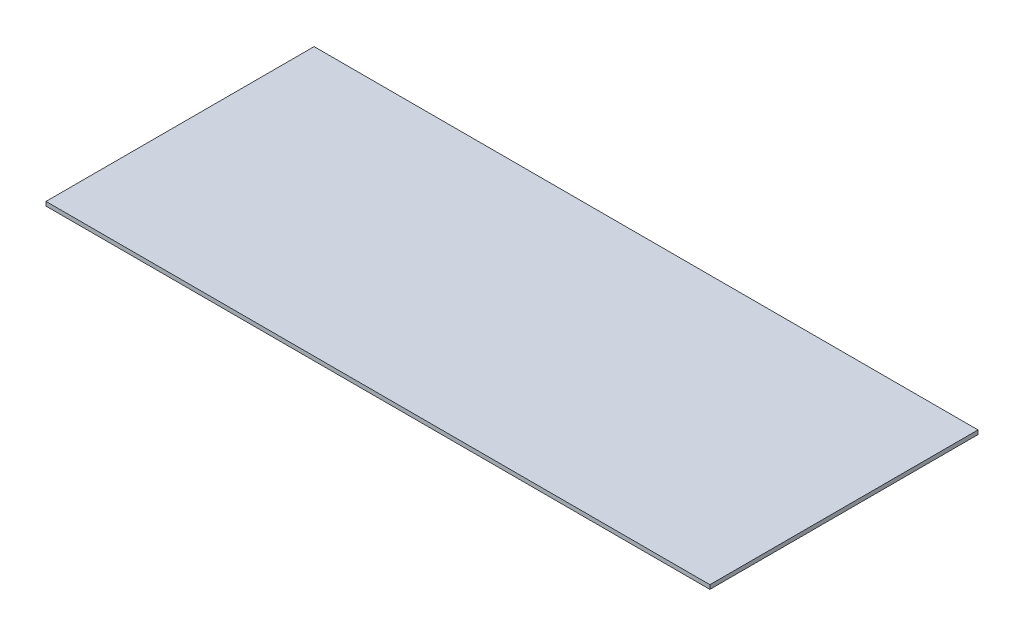
SolidWorks part; units mm, degrees
ref_plane "Front" through (0, 0, 0) normal (0, 0, 1) x (1, 0, 0)
ref_plane "Top" through (0, 0, 0) normal (0, 1, 0) x (1, 0, 0)
ref_plane "Right" through (0, 0, 0) normal (1, 0, 0) x (0, 0, -1)
sketch "Esquisse1" plane through (0, 0, 0) normal (0, 1, 0) x (1, 0, 0)
  line L1 (0, 0) -> (2600, 0)
  line L2 (0, 0) -> (0, 1050)
  line L3 (0, 1050) -> (2600, 1050)
  line L4 (2600, 0) -> (2600, 1050)
  dimension "D1" = 2600
  dimension "D2" = 1050
extrude "Boss.-Extru.1" add sketch "Esquisse1" along normal blind 16
